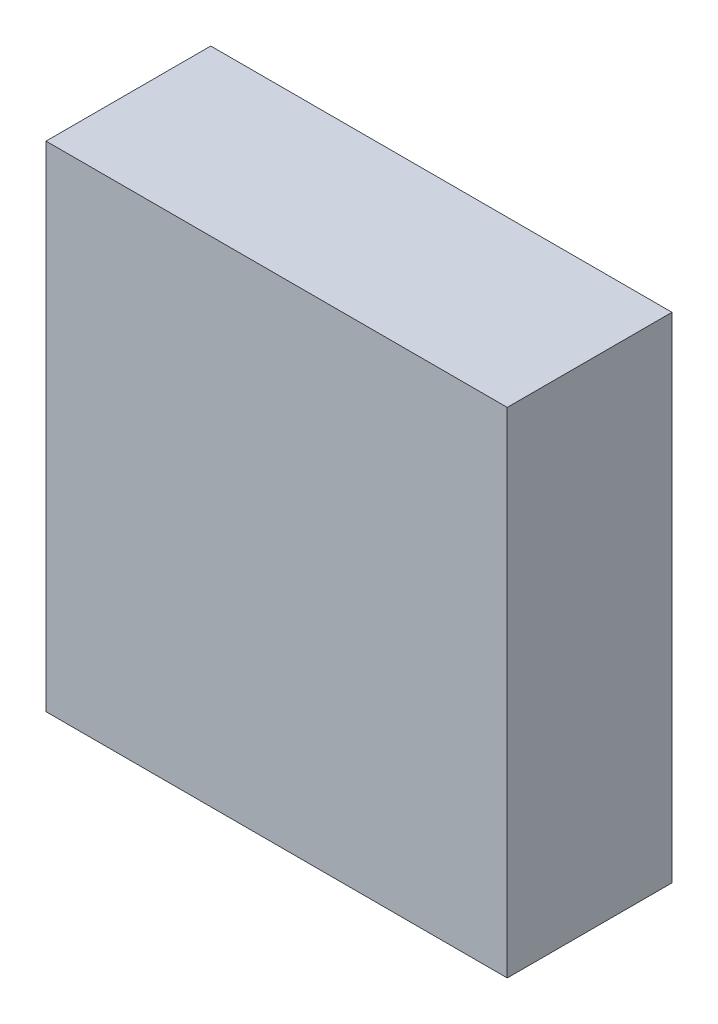
SolidWorks part; units mm, degrees
ref_plane "Front Plane" through (0, 0, 0) normal (0, 0, 1) x (1, 0, 0)
ref_plane "Top Plane" through (0, 0, 0) normal (0, 1, 0) x (1, 0, 0)
ref_plane "Right Plane" through (0, 0, 0) normal (1, 0, 0) x (0, 0, -1)
sketch "Sketch1" plane through (0, 0, 0) normal (0, 0, 1) x (1, 0, 0)
  line L0 (-1.4, 1.5) -> (1.4, 1.5)
  line L1 (1.4, 1.5) -> (1.4, -1.5)
  line L2 (1.4, -1.5) -> (-1.4, -1.5)
  line L3 (-1.4, -1.5) -> (-1.4, 1.5)
extrude "Component_Outline" add sketch "Sketch1" along normal blind 1 separate body
sketch3d "3DSketch1"
  line L0 (0, 0, 0) -> (1, 0, 0)
  line L1 (0, 0, 0) -> (0, 1, 0)
  line L2 (0, 0, 0) -> (0, 0, 1)
  point P0 (0, 0, 0)
